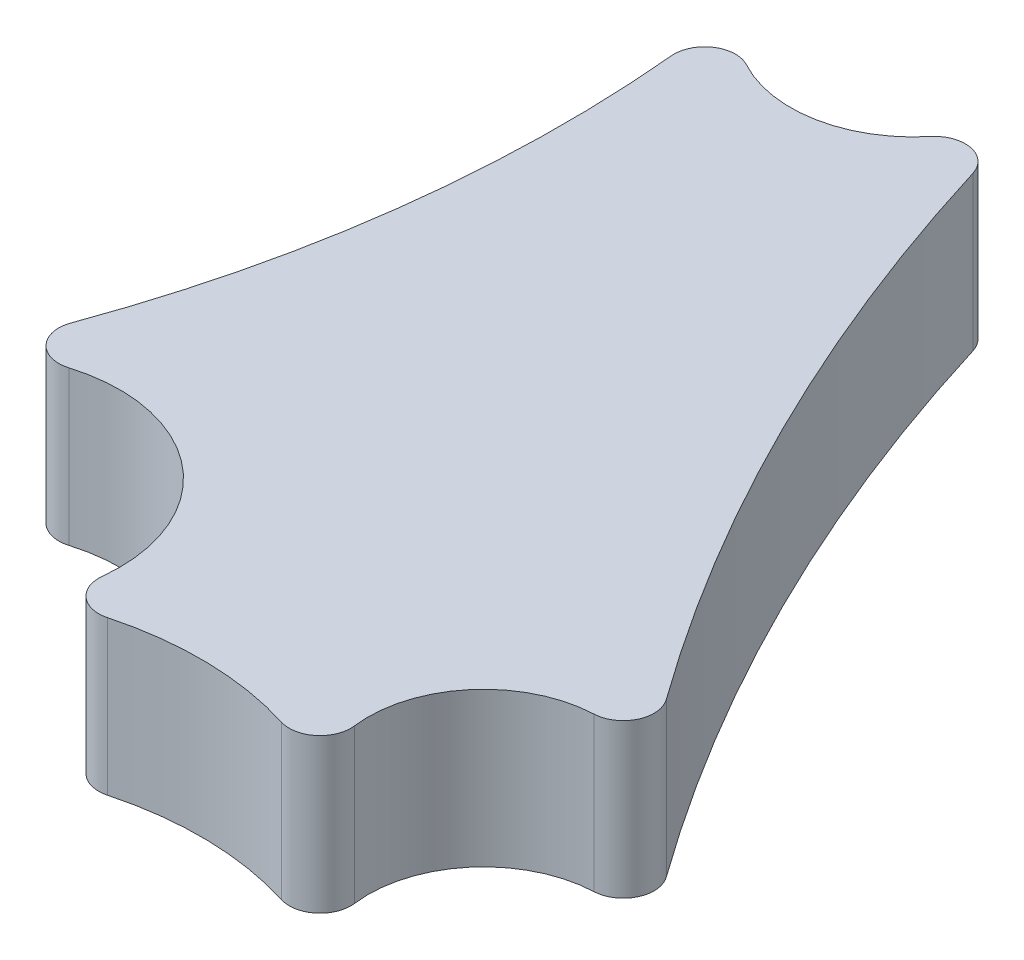
SolidWorks part; units mm, degrees
ref_plane "Front Plane" through (0, 0, 0) normal (0, 0, 1) x (1, 0, 0)
ref_plane "Top Plane" through (0, 0, 0) normal (0, 1, 0) x (1, 0, 0)
ref_plane "Right Plane" through (0, 0, 0) normal (1, 0, 0) x (0, 0, -1)
sketch "Sketch1" plane through (0, 0, 0) normal (0, 1, 0) x (1, 0, 0)
  circle A0 centre (0, 0) radius 12.7
  circle A1 centre (7.5123, 70.7221) radius 10.16
  circle A2 centre (43.1778, -0.4392) radius 9.525
  arc A3 (-2.5703, 69.4703) -> (-9.8419, 8.0266) centre (-101.3163, 50.0043) cw
  arc A4 (17.6723, 70.7221) -> (49.7515, 6.4537) centre (185.3377, 114.271) ccw
  arc A5 (11.3158, -5.7657) -> (39.2012, -9.0944) centre (22.6244, -29.496) cw
  dimension "D1" = 20.32
  dimension "D2" = 25.4
  dimension "D3" = 19.05
  dimension "D5" = 43.18
  dimension ".8" = 71.12
extrude "Boss-Extrude1" add sketch "Sketch1" along normal blind 12.7 contours A0 A5 A2 A4 A1 A3
fillet "Fillet1" radius 2.54 6 edges at (49.7515, 6.35, -6.4537) (36.341, 6.35, 7.0712) (11.3158, 6.35, 5.7657) (-9.8419, 6.35, -8.0266) (17.6723, 6.35, -70.7221) (-2.325, 6.35, -68.1818)
